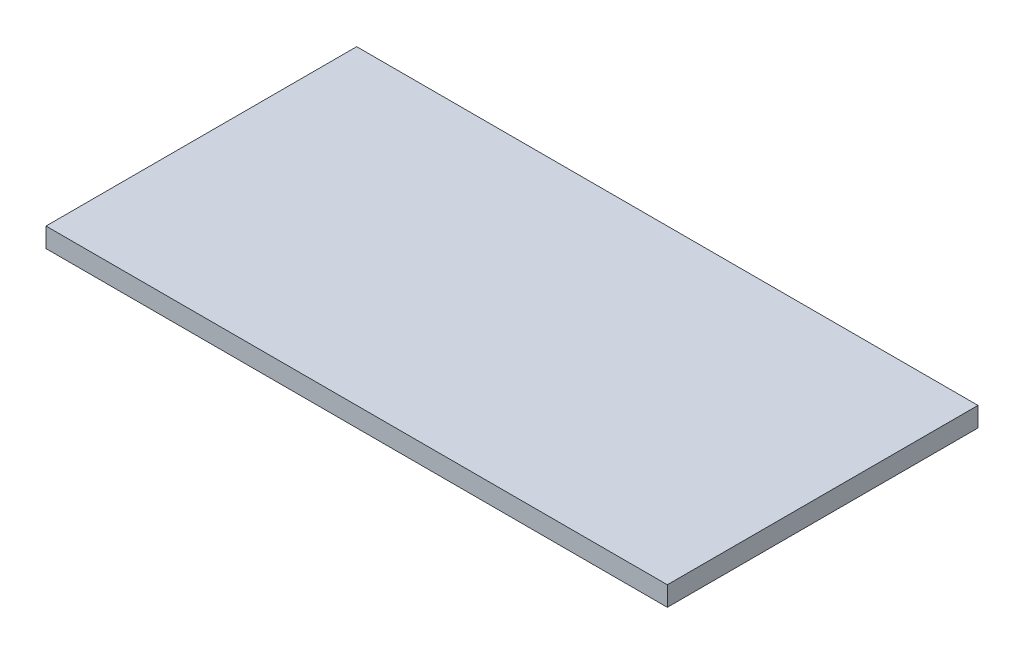
SolidWorks part; units mm, degrees
ref_plane "Front Plane" through (0, 0, 0) normal (0, 0, 1) x (1, 0, 0)
ref_plane "Top Plane" through (0, 0, 0) normal (0, 1, 0) x (1, 0, 0)
ref_plane "Right Plane" through (0, 0, 0) normal (1, 0, 0) x (0, 0, -1)
sketch "Sketch1" plane through (0, 0, 0) normal (0, 1, 0) x (1, 0, 0)
  line L1 (-25.4, -12.7) -> (25.4, -12.7)
  line L2 (-25.4, -12.7) -> (-25.4, 12.7)
  line L3 (-25.4, 12.7) -> (25.4, 12.7)
  line L4 (25.4, -12.7) -> (25.4, 12.7)
  line L5 (-25.4, -12.7) -> (25.4, 12.7) construction
  line L6 (-25.4, 12.7) -> (25.4, -12.7) construction
  point P0 (0, 0)
  dimension "D1" = 25.4
  dimension "D2" = 50.8
extrude "Boss-Extrude1" add sketch "Sketch1" along normal mid plane 1.6
